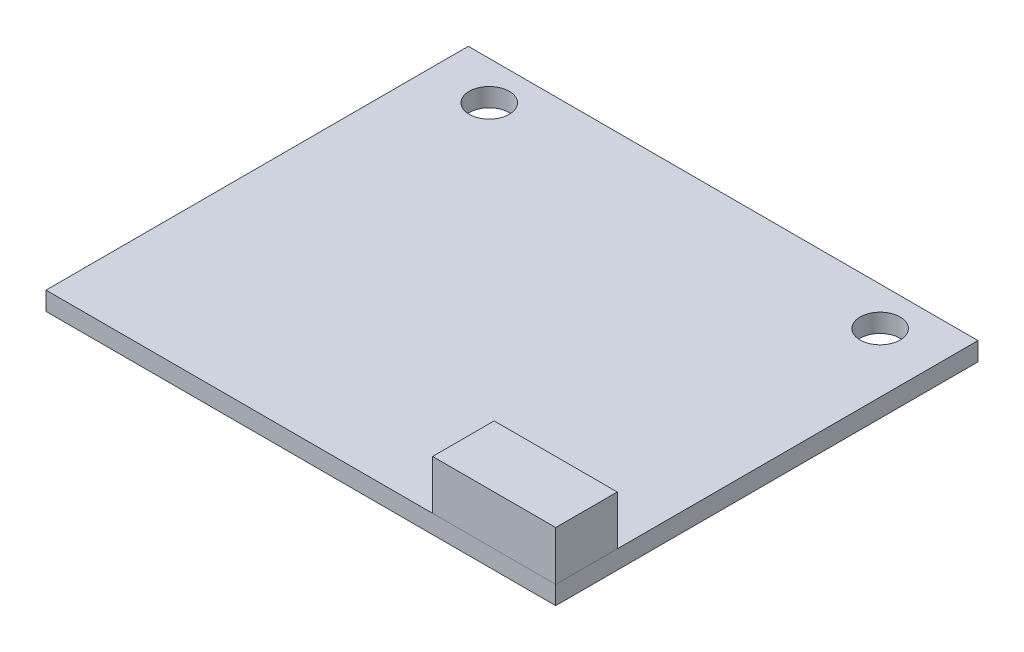
SolidWorks part; units mm, degrees
ref_plane "Přední rovina" through (0, 0, 0) normal (0, 0, 1) x (1, 0, 0)
ref_plane "Horní rovina" through (0, 0, 0) normal (0, 1, 0) x (1, 0, 0)
ref_plane "Pravá rovina" through (0, 0, 0) normal (1, 0, 0) x (0, 0, -1)
sketch "Skica1" plane through (0, 0, 0) normal (0, 1, 0) x (1, 0, 0)
  line L0 (-15.875, 14.025) -> (15.875, 14.025) construction
  line L1 (-20.7, 17.15) -> (20.7, 17.15)
  line L2 (-20.7, 17.15) -> (-20.7, -17.15)
  line L3 (-20.7, -17.15) -> (20.7, -17.15)
  line L4 (20.7, 17.15) -> (20.7, -17.15)
  circle A0 centre (-15.875, 14.025) radius 1.625
  circle A1 centre (15.875, 14.025) radius 1.625
  point P8 (-14.25, 14.025)
  point P9 (0, 14.025)
  point P10 (0, 17.15)
  point P12 (-20.7, 0)
  point P13 (-17.5, 14.025)
  point P14 (-15.875, 15.65)
  point P15 (-15.875, 12.4)
  point P16 (14.25, 14.025)
  dimension "D3" = 28.5
  dimension "D8" = 3.25
  dimension "D1" = 34.3
  dimension "D2" = 41.4
  dimension "D4" = 3.2
  dimension "D5" = 1.5
  dimension "D6" = 29.55
  dimension "D7" = 31.75
  dimension "D9" = 3.125
extrude "Přidat vysunutím1" add sketch "Skica1" along normal blind 1.5
sketch "Skica2" plane through (0, 1.5, 0) normal (0, 1, 0) x (1, 0, 0)
  line L1 (20.7, -17.15) -> (10.7, -17.15)
  line L2 (20.7, -17.15) -> (20.7, -12.15)
  line L3 (20.7, -12.15) -> (10.7, -12.15)
  line L4 (10.7, -17.15) -> (10.7, -12.15)
  dimension "D1" = 5
  dimension "D2" = 10
extrude "Přidat vysunutím2" add sketch "Skica2" along normal blind 4 separate body
